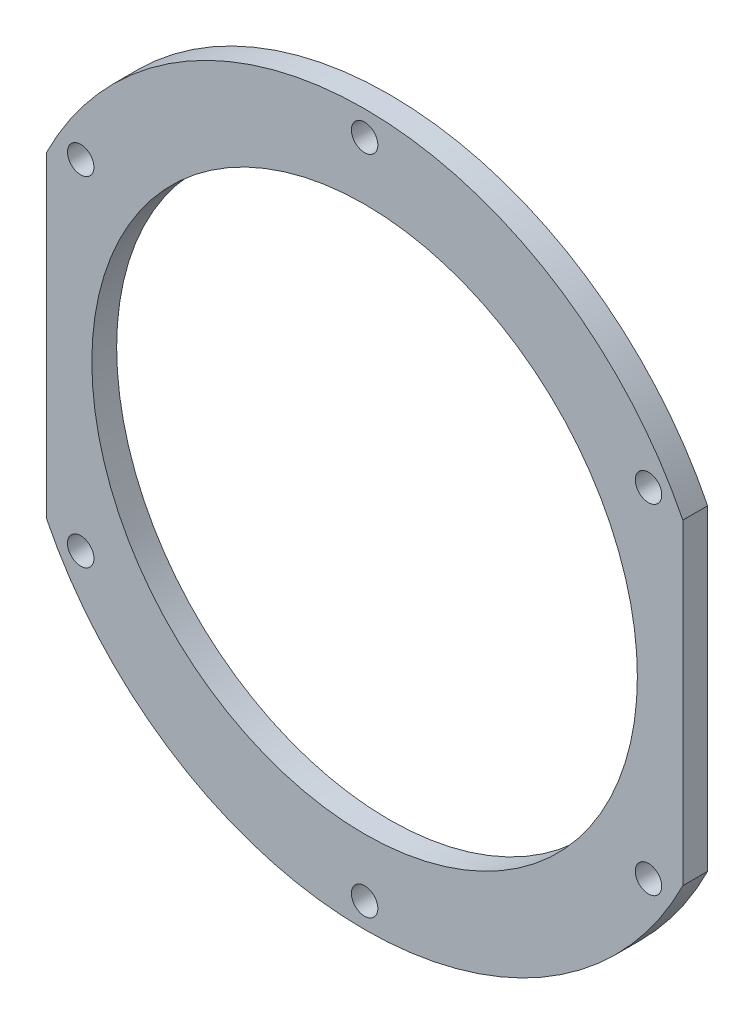
SolidWorks part; units mm, degrees
ref_plane "Ebene vorne" through (0, 0, 0) normal (0, 0, 1) x (1, 0, 0)
ref_plane "Ebene oben" through (0, 0, 0) normal (0, 1, 0) x (1, 0, 0)
ref_plane "Ebene rechts" through (0, 0, 0) normal (1, 0, 0) x (0, 0, -1)
sketch "Skizze1" plane through (0, 0, 0) normal (0, 0, 1) x (1, 0, 0)
  line L0 (0, 0) -> (0, 22.2518) construction
  line L2 (-38.5, -19.1507) -> (-38.5, 19.1507)
  line L4 (38.5, -19.1507) -> (38.5, 19.1507)
  circle A0 centre (0, 0) radius 33
  arc A1 (-38.5, -19.1507) -> (38.5, -19.1507) centre (0, 0) ccw
  arc A2 (38.5, 19.1507) -> (-38.5, 19.1507) centre (0, 0) ccw
  dimension "D1" = 66
  dimension "D4" = 86
  dimension "D2" = 77
extrude "Aufsatz-Linear austragen1" add sketch "Skizze1" along normal blind 3
hole_wizard "Ø3.2 (3.2) Durchmesser Bohrung1" positions "Skizze4" profile "Skizze5" hole size "Ø3.2" standard "DIN" end condition through all
sketch "Skizze4" plane through (0, 0, 3) normal (0, 0, 1) x (1, 0, 0)
  line L0 (0, 0) -> (-50000, 0) construction
  line L1 (0, 0) -> (0, -50000) construction
  circle A0 centre (0, 0) radius 40 construction
  point P5 (0, 40)
  point P7 (0, -40)
  point P20 (34.3475, -20.5)
  point P23 (34.3475, 20.5)
  point P24 (-34.3475, -20.5)
  point P25 (-34.3475, 20.5)
  dimension "D1" = 80
  dimension "D2" = 20.5
sketch "Skizze5" plane through (-34.3475, 20.5, 3) normal (1, 0, 0) x (0, -1, 0)
  line L0 (0, 0) -> (0, 3)
  line L1 (0, 3) -> (1.6, 3)
  line L2 (1.6, 3) -> (1.6, 0)
  line L5 (1.6, 0) -> (0, 0)
  line L11 (0, -6.35) -> (0, 107.95) construction
  dimension "Bohrerdurchmesser" = 3.2
  dimension "Bohrungstiefe" = 3
